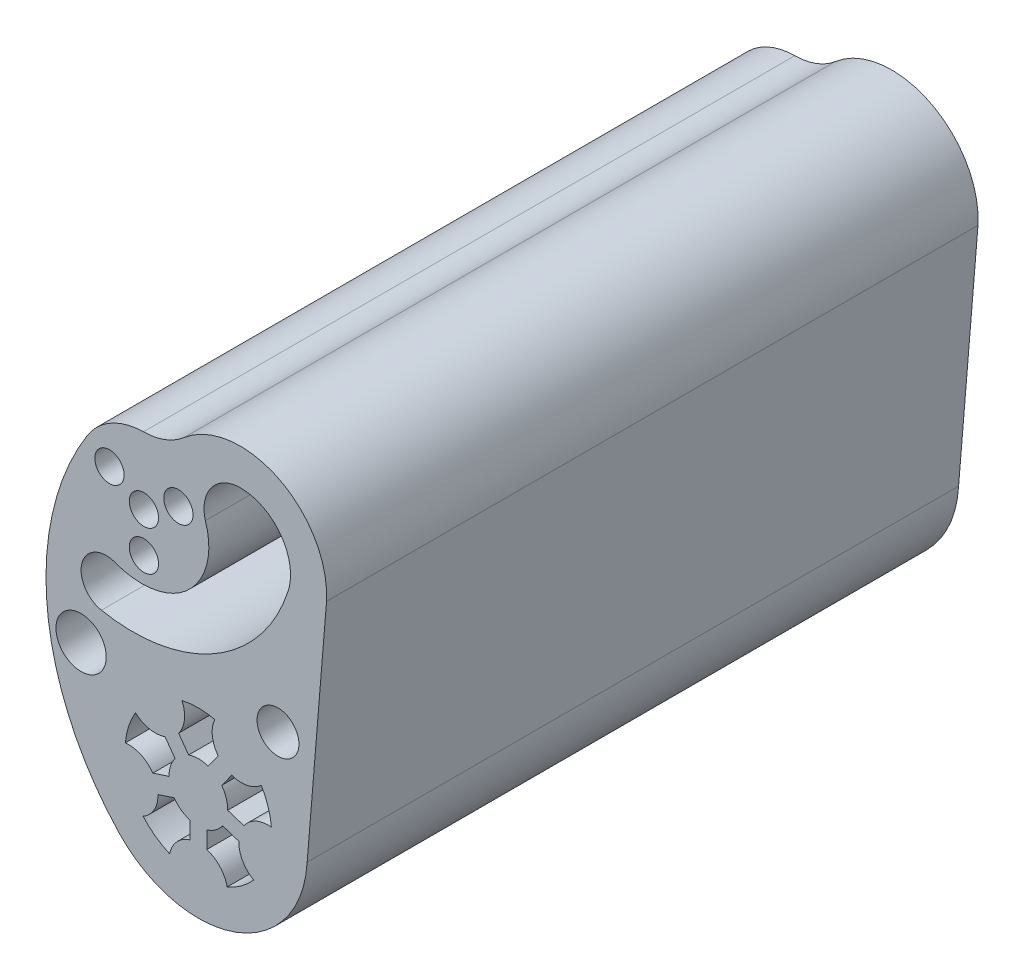
SolidWorks part; units mm, degrees
ref_plane "Спереди" through (0, 0, 0) normal (0, 0, 1) x (1, 0, 0)
ref_plane "Сверху" through (0, 0, 0) normal (0, 1, 0) x (1, 0, 0)
ref_plane "Справа" through (0, 0, 0) normal (1, 0, 0) x (0, 0, -1)
sketch "Эскиз1" plane through (0, 0, 0) normal (0, 0, 1) x (1, 0, 0)
  line L0 (110.946, 0) -> (-110.946, 0) construction
  line L1 (0, -222.9573) -> (0, 222.9573) construction
  line L2 (-4, -13.4164) -> (-4, -21.5836)
  line L3 (4, -13.4164) -> (4, -21.5836)
  line L4 (-13.9958, -0.3417) -> (-21.7633, -2.8655)
  line L5 (-11.5237, -7.9501) -> (-19.2911, -10.4739)
  line L6 (-4.6499, 13.2052) -> (-9.4504, 19.8126)
  line L7 (-11.122, 8.503) -> (-15.9226, 15.1104)
  line L8 (11.122, 8.503) -> (15.9226, 15.1104)
  line L9 (4.6499, 13.2052) -> (9.4504, 19.8126)
  line L10 (11.5237, -7.9501) -> (19.2911, -10.4739)
  line L11 (13.9958, -0.3417) -> (21.7633, -2.8655)
  line L12 (38, 73.032) -> (38, 8.4771) construction
  line L13 (56, 44) -> (20, 44) construction
  line L14 (20, 216.1185) -> (20, 97.5396) construction
  line L15 (0.2805, 112) -> (39.7195, 112) construction
  line L16 (-26, 64.1259) -> (-26, 157.0064) construction
  line L17 (4, 104) -> (-56, 104) construction
  line L18 (-56, 17.8471) -> (-56, 50.1529) construction
  line L19 (-44, 37.5762) -> (-44, 69.4625) construction
  line L20 (-45.7046, 34) -> (-87.7576, 34) construction
  line L21 (-28.6332, 64) -> (-59.3668, 64) construction
  line L22 (51.921, -2.8655) -> (61.181, 109.6072)
  line L23 (-26, 104) -> (-26, 85) construction
  arc A0 (13.7171, -32.2) -> (26.3852, -22.9961) centre (0, 0) ccw
  arc A1 (4, -13.4164) -> (11.5237, -7.9501) centre (0, 0) ccw
  arc A2 (13.7171, -32.2) -> (4, -21.5836) centre (0, -35) ccw
  arc A3 (-4, -21.5836) -> (-13.7171, -32.2) centre (0, -35) ccw
  arc A4 (-21.7633, -2.8655) -> (-34.8628, 3.0954) centre (-33.287, -10.8156) ccw
  arc A5 (-26.3852, -22.9961) -> (-19.2911, -10.4739) centre (-33.287, -10.8156) ccw
  arc A6 (-9.4504, 19.8126) -> (-7.8293, 34.1131) centre (-20.5725, 28.3156) ccw
  arc A7 (-30.0241, 17.9876) -> (-15.9226, 15.1104) centre (-20.5725, 28.3156) ccw
  arc A8 (15.9226, 15.1104) -> (30.0241, 17.9876) centre (20.5725, 28.3156) ccw
  arc A9 (7.8293, 34.1131) -> (9.4504, 19.8126) centre (20.5725, 28.3156) ccw
  arc A10 (19.2911, -10.4739) -> (26.3852, -22.9961) centre (33.287, -10.8156) ccw
  arc A11 (34.8628, 3.0954) -> (21.7633, -2.8655) centre (33.287, -10.8156) ccw
  arc A12 (-26.3852, -22.9961) -> (-13.7171, -32.2) centre (0, 0) ccw
  arc A13 (-30.0241, 17.9876) -> (-34.8628, 3.0954) centre (0, 0) ccw
  arc A14 (7.8293, 34.1131) -> (-7.8293, 34.1131) centre (0, 0) ccw
  arc A15 (34.8628, 3.0954) -> (30.0241, 17.9876) centre (0, 0) ccw
  arc A16 (-11.5237, -7.9501) -> (-4, -13.4164) centre (0, 0) ccw
  arc A17 (-11.122, 8.503) -> (-13.9958, -0.3417) centre (0, 0) ccw
  arc A18 (4.6499, 13.2052) -> (-4.6499, 13.2052) centre (0, 0) ccw
  arc A19 (13.9958, -0.3417) -> (11.122, 8.503) centre (0, 0) ccw
  circle A20 centre (0, 0) radius 35 construction
  circle A23 centre (-26, 104) radius 19 construction
  circle A24 centre (-26, 104) radius 7
  arc A28 (-18.7583, 73.8577) -> (3.3235, 114.0566) centre (-26, 104) ccw
  arc A29 (20, 136) -> (3.3235, 114.0566) centre (20, 118.6914) ccw
  circle A31 centre (-56, 34) radius 12
  arc A32 (-39.72, 75.2108) -> (-46.3038, 52.2232) centre (-44, 64) ccw
  arc A33 (-39.72, 75.2108) -> (-18.7583, 73.8577) centre (-27.054, 108.3869) ccw
  arc A37 (61.181, 109.6072) -> (-6.9123, 143.2622) centre (20, 112) ccw
  arc A38 (-26, 136) -> (-53.1343, 120.9627) centre (-26, 104) ccw
  arc A40 (-37.9875, -35.5099) -> (51.921, -2.8655) centre (0, 0) ccw
  arc A41 (-26.2502, 135.999) -> (-6.9123, 143.2622) centre (-26.4847, 165.9981) ccw
  arc A42 (-53.1343, 120.9627) -> (-37.9875, -35.5099) centre (56.2507, 52.5819) ccw
  circle A43 centre (38, 44) radius 10
  circle A44 centre (-26, 85) radius 7
  circle A45 centre (-42.4545, 113.5) radius 7
  circle A46 centre (-9.5455, 113.5) radius 7
  arc A47 (42.813, 104.5456) -> (20, 136) centre (20, 112) ccw
  arc A48 (-46.3038, 52.2232) -> (42.813, 104.5456) centre (-31.3292, 128.7723) ccw
  point P4 (0, 0)
  point P8 (0, 0)
  point P46 (0, 0)
  point P50 (38, 44)
  point P51 (38, 44)
  point P58 (20, 112)
  point P65 (-26, 104)
  point P76 (-26, 104)
  point P86 (-56, 34)
  point P91 (-44, 64)
  point P114 (0, -198.8339)
  dimension "D1" = 70
  dimension "D2" = 28
  dimension "D3" = 5
  dimension "D6" = 20
  dimension "D9" = 24
  dimension "D12" = 14
  dimension "D13" = 34
  dimension "D14" = 12
  dimension "D15" = 14
  dimension "D16" = 129
  dimension "D17" = 30
  dimension "D18" = 30
  dimension "D19" = 78
  dimension "D20" = 24
  dimension "D21" = 3
  dimension "D7" = 38
  dimension "D22" = 14
  dimension "D23" = 17.3086
  dimension "D24" = 31
  dimension "D25" = 35.5118
  dimension "D26" = 30
  dimension "D27" = 32
  dimension "D28" = 52
  dimension "D29" = 112.4727
  dimension "D30" = 8
  dimension "D31" = 26
  dimension "D36" = 35
  dimension "D37" = 19
  dimension "D55" = 24.7723
  dimension "D56" = 24.1234
  dimension "D4" = 44
  dimension "D5" = 38
  dimension "D8" = 68
  dimension "D10" = 46
  dimension "D11" = 8
  dimension "D32" = 51.981
  dimension "D33" = 18
  dimension "D34" = 6.6914
  dimension "D35" = 0.4847
  dimension "D38" = 19
  dimension "D39" = 221.8919
  dimension "D40" = 32.3058
  dimension "D41" = 42.053
  dimension "D42" = 64.555
  dimension "D43" = 30.7335
  dimension "D44" = 31.8863
  dimension "D45" = 60
  dimension "D46" = 118.5789
  dimension "D47" = 39.4389
  dimension "D48" = 92.8805
  dimension "D49" = 445.9145
  dimension "D50" = 31.7576
  dimension "D51" = 5.4625
  dimension "D52" = 29.032
  dimension "D53" = 104.1185
  dimension "D54" = 53.0064
extrude "Бобышка-Вытянуть1" add sketch "Эскиз1" along normal blind 311
